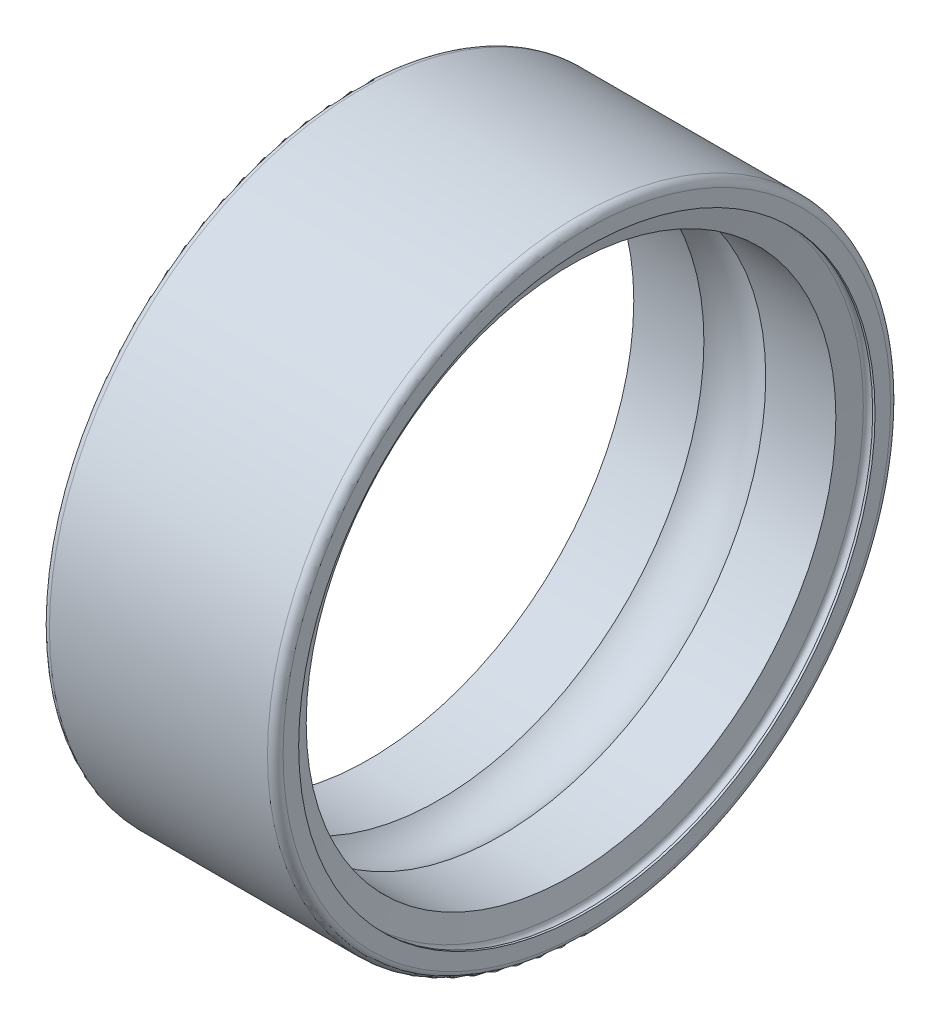
SolidWorks part; units mm, degrees
ref_plane "Front Plane" through (0, 0, 0) normal (0, 0, 1) x (1, 0, 0)
ref_plane "Top Plane" through (0, 0, 0) normal (0, 1, 0) x (1, 0, 0)
ref_plane "Right Plane" through (0, 0, 0) normal (1, 0, 0) x (0, 0, -1)
ref_plane "Plane1" through (0, 0, 0) normal (0, 0, 1) x (1, 0, 0)
sketch "Sketch1" plane through (0, 0, 0) normal (0, 0, 1) x (1, 0, 0)
  line L0 (0, 3.9) -> (0, 3.7)
  line L1 (0, 3.7) -> (0.03, 3.7)
  line L2 (0.15, 3.7) -> (0.2029, 3.4)
  line L3 (0.2029, 3.4) -> (1.1031, 3.4)
  line L4 (1.8969, 3.4) -> (2.7971, 3.4)
  line L5 (2.7971, 3.4) -> (2.85, 3.7)
  line L6 (2.97, 3.7) -> (3, 3.7)
  line L7 (3, 3.7) -> (3, 3.9)
  line L8 (2.9, 4) -> (0.1, 4)
  line L9 (50, 0) -> (-50, 0) construction
  arc A0 (0.03, 3.7) -> (0.15, 3.7) centre (0.09, 3.7) cw
  arc A1 (1.1031, 3.4) -> (1.8969, 3.4) centre (1.5, 2.95) cw
  arc A2 (2.85, 3.7) -> (2.97, 3.7) centre (2.91, 3.7) cw
  arc A3 (3, 3.9) -> (2.9, 4) centre (2.9, 3.9) ccw
  arc A4 (0.1, 4) -> (0, 3.9) centre (0.1, 3.9) ccw
revolve "Revolve1" add sketch "Sketch1" angle 360 about L9
